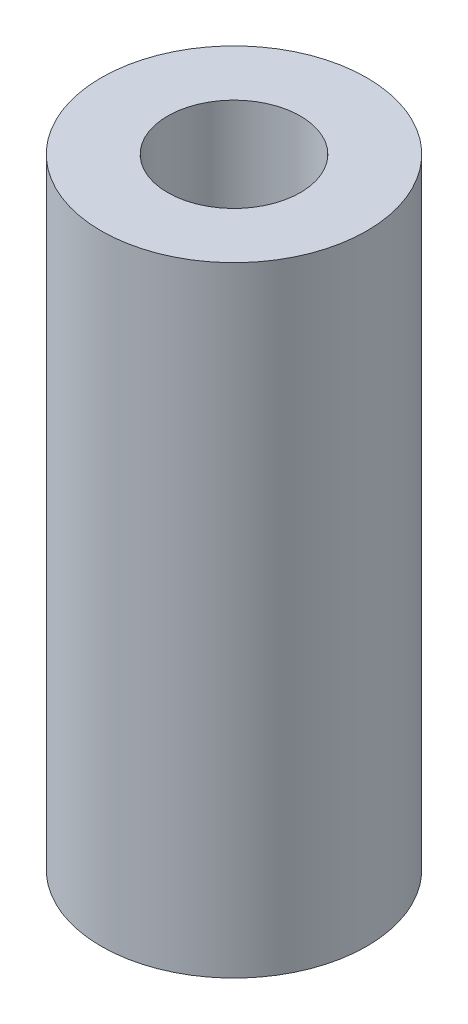
SolidWorks part; units mm, degrees
material "AISI 304"
ref_plane "前视基准面" through (0, 0, 0) normal (0, 0, 1) x (1, 0, 0)
ref_plane "上视基准面" through (0, 0, 0) normal (0, 1, 0) x (1, 0, 0)
ref_plane "右视基准面" through (0, 0, 0) normal (1, 0, 0) x (0, 0, -1)
other "Configuration Table"
sketch "草图1" plane through (0, 0, 0) normal (0, 1, 0) x (1, 0, 0)
  circle A0 centre (0, 0) radius 6
  circle A1 centre (0, 0) radius 3
  dimension "D1" = 12
  dimension "D2" = 6
extrude "凸台-拉伸1" add sketch "草图1" along normal blind 28
